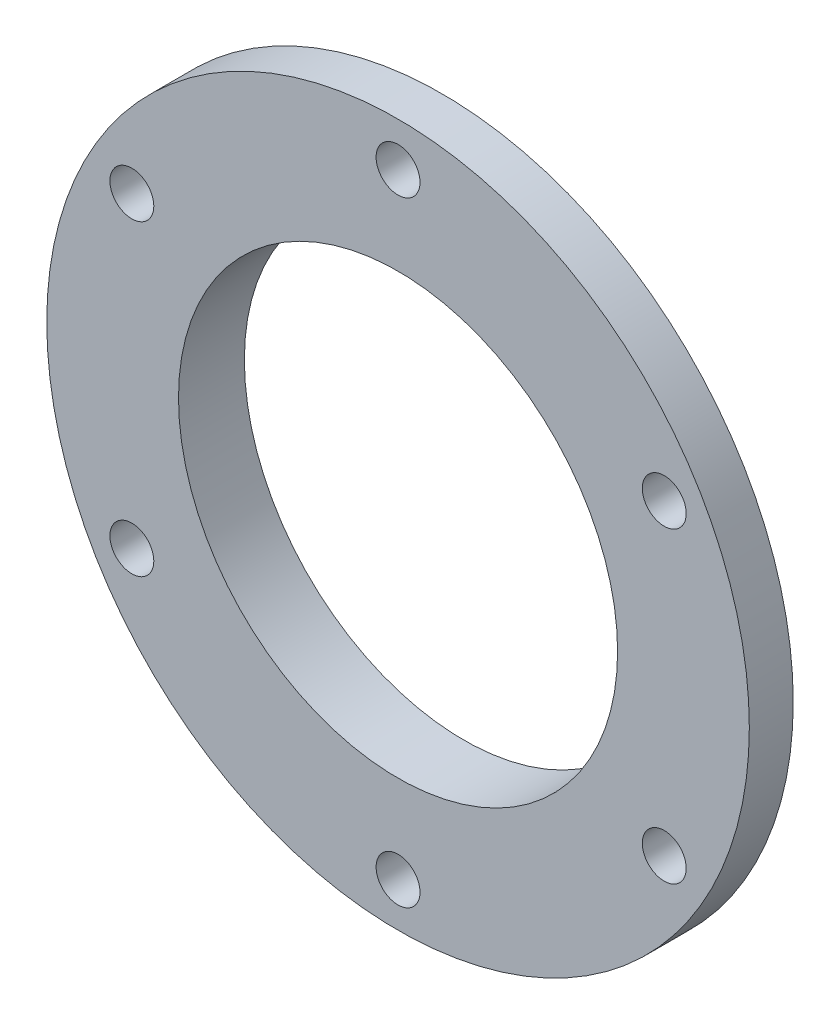
SolidWorks part; units mm, degrees
ref_plane "Front Plane" through (0, 0, 0) normal (0, 0, 1) x (1, 0, 0)
ref_plane "Top Plane" through (0, 0, 0) normal (0, 1, 0) x (1, 0, 0)
ref_plane "Right Plane" through (0, 0, 0) normal (1, 0, 0) x (0, 0, -1)
sketch "Sketch1" plane through (0, 0, 0) normal (0, 0, 1) x (1, 0, 0)
  circle A0 centre (0, 0) radius 40
  circle A1 centre (0, 0) radius 25
  dimension "D1" = 80
  dimension "D2" = 50
extrude "Boss-Extrude1" add sketch "Sketch1" along normal blind 5
sketch "Sketch3" plane through (0, 0, 0) normal (0, 0, -1) x (-1, 0, 0)
  circle A0 centre (0, 0) radius 30
  circle A2 centre (0, 0) radius 25
  circle A4 centre (0, 0) radius 25 construction
  dimension "D1" = 5
extrude "slew bearing lip" add sketch "Sketch3" along normal blind 2.5
sketch "Sketch4" plane through (0, 0, 0) normal (0, 0, 1) x (1, 0, 0)
  circle A0 centre (0, 0) radius 35 construction
  circle A1 centre (0, 35) radius 2.5
  circle A2 centre (30.3109, 17.5) radius 2.5
  circle A3 centre (30.3109, -17.5) radius 2.5
  circle A4 centre (0, -35) radius 2.5
  circle A5 centre (-30.3109, -17.5) radius 2.5
  circle A6 centre (-30.3109, 17.5) radius 2.5
  point P5 (-29.7321, 18.4662)
  point P6 (-30.1838, -17.7183)
  dimension "D1" = 70
  dimension "D2" = 5
  dimension "D3" = 6
extrude "screw holes" cut sketch "Sketch4" along normal through all
